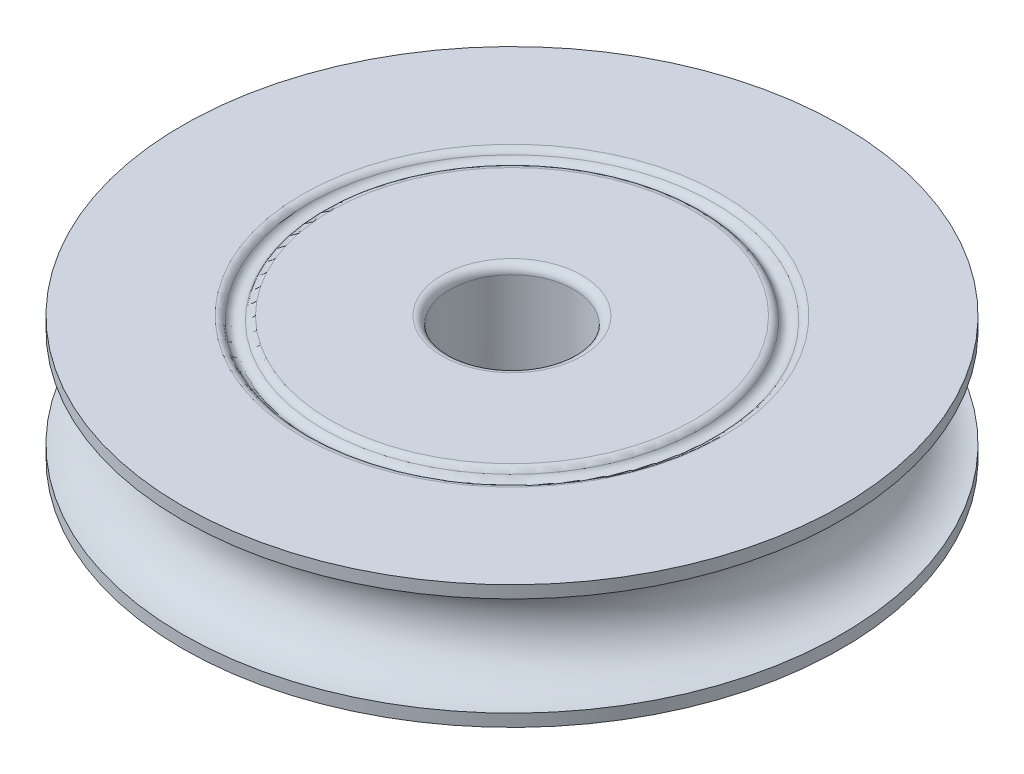
SolidWorks part; units mm, degrees
ref_plane "Front Plane" through (0, 0, 0) normal (0, 0, 1) x (1, 0, 0)
ref_plane "Top Plane" through (0, 0, 0) normal (0, 1, 0) x (1, 0, 0)
ref_plane "Right Plane" through (0, 0, 0) normal (1, 0, 0) x (0, 0, -1)
sketch "Sketch1" plane through (0, 0, 0) normal (1, 0, 0) x (0, 0, -1)
  line L1 (-7.5, -7.5) -> (-22.75, -7.5)
  line L4 (-40, 7.5) -> (-24.75, 7.5)
  line L6 (-7.5, 7.5) -> (-7.5, -7.5)
  line L7 (-40, 7.5) -> (-40, 6)
  line L8 (-40, -6) -> (-40, -7.5)
  line L9 (0, 11.6986) -> (0, -11.6986) construction
  line L10 (-22.75, 7.5) -> (-7.5, 7.5)
  line L11 (22, 0) -> (-22, 0) construction
  line L12 (-24.75, -7.5) -> (-40, -7.5)
  arc A1 (-40, 6) -> (-40, -6) centre (-40, 0) cw
  arc A2 (-24.75, 7.5) -> (-22.75, 7.5) centre (-23.75, 7.5) ccw
  arc A3 (-24.75, -7.5) -> (-22.75, -7.5) centre (-23.75, -7.5) cw
  point P2 (-7.5, 0)
  point P13 (0, 0)
  dimension "D3" = 15
  dimension "D4" = 6
  dimension "D5" = 2
  dimension "D1" = 32.5
  dimension "D2" = 7.5
  dimension "D6" = 23.75
  dimension "D7" = 40
revolve "Revolve1" add sketch "Sketch1" angle 360 about L9
fillet "Fillet2" radius 1 4 edges at (0, -7.5, 24.75) (0, -7.5, 22.75) (0, 7.5, 22.75) (0, 7.5, 24.75)
fillet "Fillet3" radius 1 2 edges at (0, -7.5, 7.5) (0, 7.5, 7.5)
